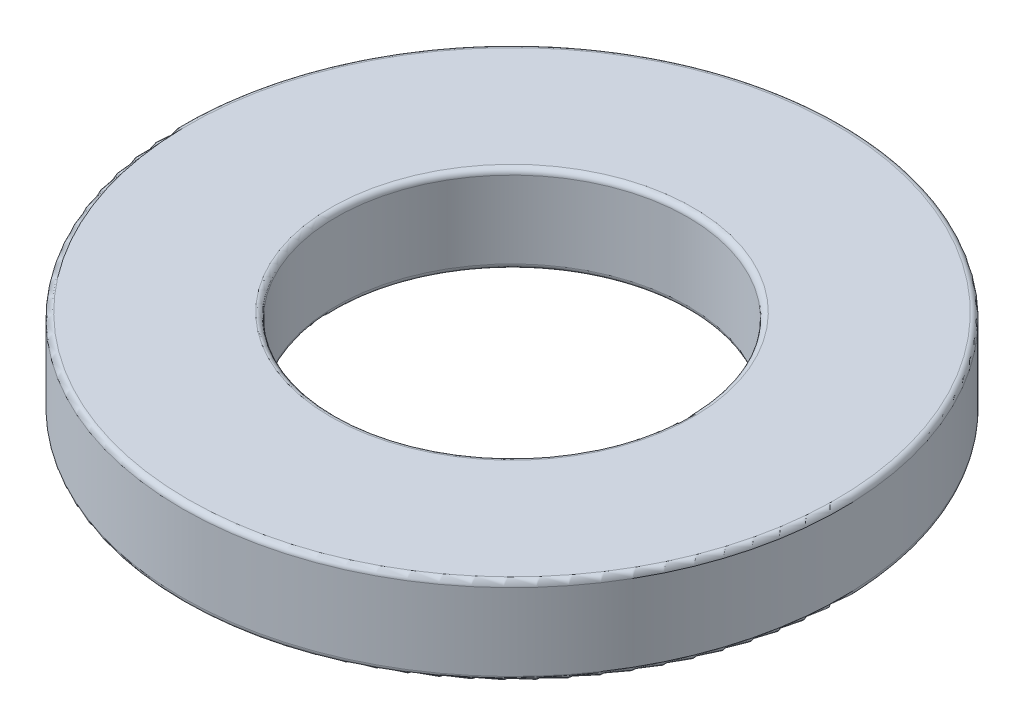
SolidWorks part; units mm, degrees
ref_plane "Front Plane" through (0, 0, 0) normal (0, 0, 1) x (1, 0, 0)
ref_plane "Top Plane" through (0, 0, 0) normal (0, 1, 0) x (1, 0, 0)
ref_plane "Right Plane" through (0, 0, 0) normal (1, 0, 0) x (0, 0, -1)
sketch "Sketch1" plane through (0, 0, 0) normal (0, 1, 0) x (1, 0, 0)
  circle A0 centre (0, 0) radius 6
  circle A1 centre (0, 0) radius 3.2
  dimension "D1" = 12
  dimension "D2" = 6.4
extrude "Boss-Extrude1" add sketch "Sketch1" along normal mid plane 1.6
fillet "Fillet1" radius 0.1 4 edges at (0, -0.8, 3.2) (0, -0.8, 6) (0, 0.8, 3.2) (0, 0.8, 6)
